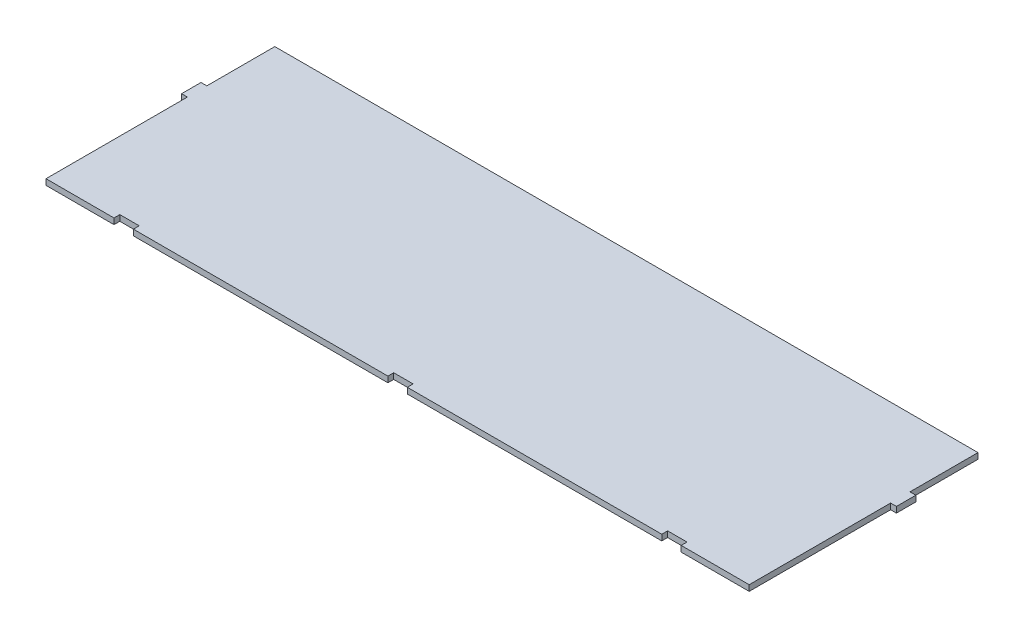
SolidWorks part; units mm, degrees
ref_plane "Front Plane" through (0, 0, 0) normal (0, 0, 1) x (1, 0, 0)
ref_plane "Top Plane" through (0, 0, 0) normal (0, 1, 0) x (1, 0, 0)
ref_plane "Right Plane" through (0, 0, 0) normal (1, 0, 0) x (0, 0, -1)
sketch "Sketch1" plane through (0, 0, 0) normal (0, 1, 0) x (1, 0, 0)
  line L0 (-184, 33.695) -> (-181, 33.695)
  line L1 (181, 68.695) -> (-181, 68.695)
  line L2 (184, 33.695) -> (184, 23.695)
  line L3 (181, -49.095) -> (146, -49.095)
  line L4 (-184, 33.695) -> (-184, 23.695)
  line L5 (-146, -49.095) -> (-146, -46.095)
  line L6 (-146, -46.095) -> (-136, -46.095)
  line L7 (-181, 68.695) -> (-181, 33.695)
  line L8 (-181, 23.695) -> (-184, 23.695)
  line L9 (184, 33.695) -> (181, 33.695)
  line L10 (181, 68.695) -> (181, 33.695)
  line L11 (181, 23.695) -> (184, 23.695)
  line L12 (-181, 23.695) -> (-181, -49.095)
  line L13 (181, 23.695) -> (181, -49.095)
  line L14 (-136, -46.095) -> (-136, -49.095)
  line L15 (146, -49.095) -> (146, -46.095)
  line L16 (146, -46.095) -> (136, -46.095)
  line L17 (136, -46.095) -> (136, -49.095)
  line L18 (-5, -46.095) -> (5, -46.095)
  line L19 (5, -46.095) -> (5, -49.095)
  line L20 (-5, -46.095) -> (-5, -49.095)
  line L21 (-5, -49.095) -> (-136, -49.095)
  line L22 (-146, -49.095) -> (-181, -49.095)
  line L23 (136, -49.095) -> (5, -49.095)
  point P0 (0, 0)
  dimension "D1" = 3
  dimension "D2" = 35
  dimension "D3" = 3
  dimension "D4" = 35
  dimension "D5" = 10
  dimension "D6" = 3
  dimension "D7" = 35
  dimension "D8" = 10
  dimension "D9" = 10
  dimension "D10" = 368
  dimension "D11" = 117.79
  dimension "D12" = 35
  dimension "D13" = 10
  dimension "D14" = 3
  dimension "D15" = 10
  dimension "D16" = 72.79
  dimension "D17" = 3
extrude "Boss-Extrude1" add sketch "Sketch1" along normal blind 3
